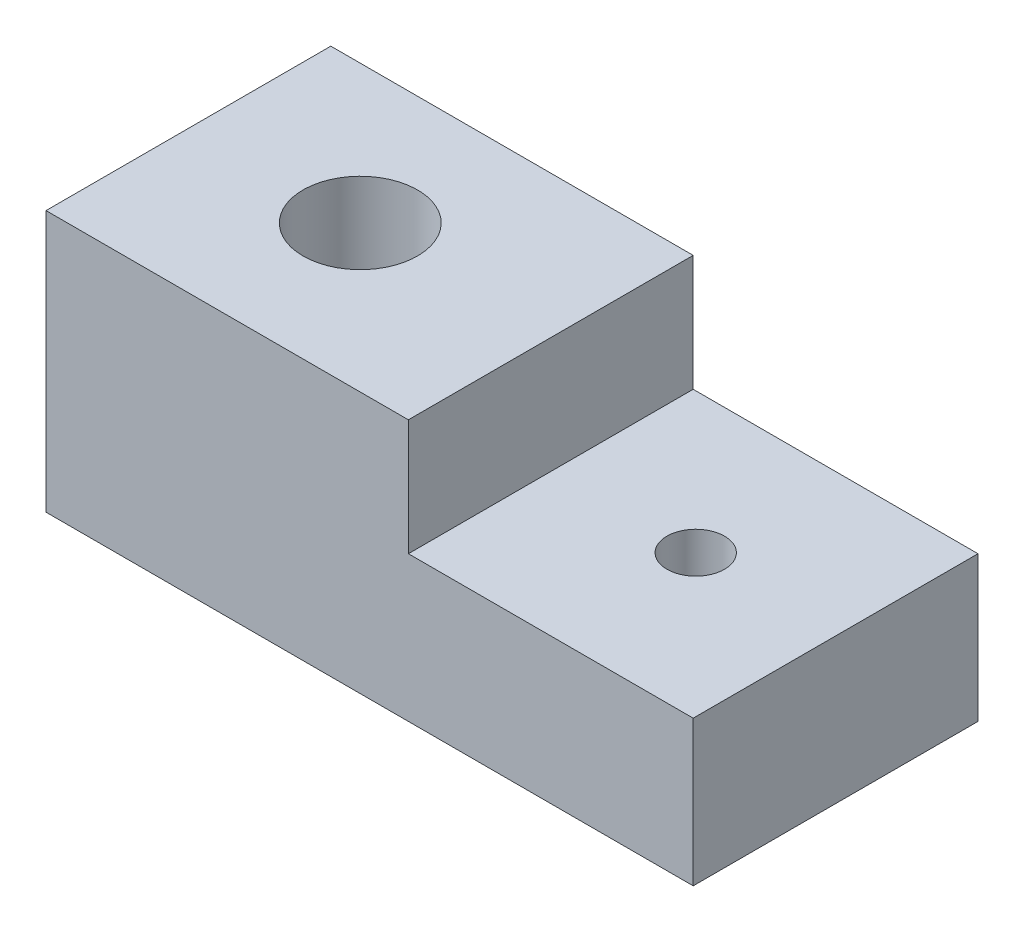
SolidWorks part; units mm, degrees
ref_plane "Front Plane" through (0, 0, 0) normal (0, 0, 1) x (1, 0, 0)
ref_plane "Top Plane" through (0, 0, 0) normal (0, 1, 0) x (1, 0, 0)
ref_plane "Right Plane" through (0, 0, 0) normal (1, 0, 0) x (0, 0, -1)
sketch "Sketch1" plane through (0, 0, 0) normal (0, 0, 1) x (1, 0, 0)
  line L1 (0, 0) -> (127.2354, 0)
  line L2 (0, 0) -> (0, 91.7195)
  line L3 (0, 91.7195) -> (127.2354, 91.7195)
  line L4 (127.2354, 0) -> (127.2354, 91.7195)
extrude "Boss-Extrude1" add sketch "Sketch1" along normal blind 100
sketch "Sketch2" plane through (127.2354, 0, 0) normal (1, 0, 0) x (0, 0, -1)
  line L0 (-100, 0) -> (-100, 91.7195) construction
  line L1 (-100, 50.9963) -> (0, 50.9963)
  line L2 (-100, 50.9963) -> (-100, 0)
  line L3 (-100, 0) -> (0, 0)
  line L4 (0, 50.9963) -> (0, 0)
extrude "Boss-Extrude2" add sketch "Sketch2" along normal blind 100
hole_wizard "Ø1.0mm Dowel Hole1" positions "Sketch5" profile "Sketch4" hole size "Ø1.0" standard "ISO" end condition through all
sketch "Sketch5" plane through (0, 50.9963, 0) normal (0, 1, 0) x (1, 0, 0)
  point P0 (177.3744, -49.2436)
sketch "Sketch4" plane through (177.3744, 50.9963, 49.2436) normal (1, 0, 0) x (0, 0, 1)
  line L0 (0, 0) -> (0, 50.9963)
  line L1 (0, 50.9963) -> (10.1, 50.9963)
  line L2 (10.1, 50.9963) -> (10.1, 0)
  line L5 (10.1, 0) -> (0, 0)
  line L11 (0, -6.35) -> (0, 107.95) construction
  dimension "Thru Hole Dia." = 20.2
  dimension "Thru Hole Depth" = 50.9963
hole_wizard "Ø1.0mm Dowel Hole2" positions "Sketch6" profile "Sketch7" hole size "Ø1.0" standard "ISO" end condition through all
sketch "Sketch6" plane through (0, 91.7195, 0) normal (0, 1, 0) x (1, 0, 0)
  point P0 (58.9383, -48.5952)
sketch "Sketch7" plane through (58.9383, 91.7195, 48.5952) normal (1, 0, 0) x (0, 0, 1)
  line L0 (0, 0) -> (0, 91.7195)
  line L1 (0, 91.7195) -> (20.1, 91.7195)
  line L2 (20.1, 91.7195) -> (20.1, 0)
  line L5 (20.1, 0) -> (0, 0)
  line L11 (0, -6.35) -> (0, 107.95) construction
  dimension "Thru Hole Dia." = 40.2
  dimension "Thru Hole Depth" = 91.7195
